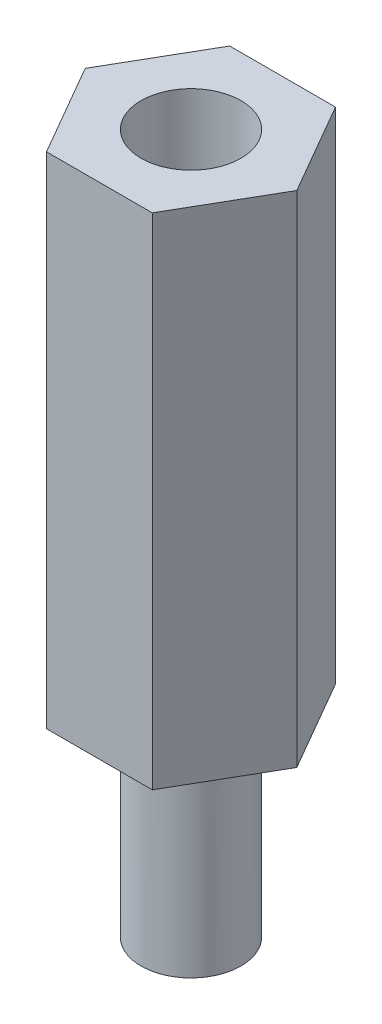
SolidWorks part; units mm, degrees
ref_plane "Plan de face" through (0, 0, 0) normal (0, 0, 1) x (1, 0, 0)
ref_plane "Plan de dessus" through (0, 0, 0) normal (0, 1, 0) x (1, 0, 0)
ref_plane "Plan de droite" through (0, 0, 0) normal (1, 0, 0) x (0, 0, -1)
sketch "Esquisse1" plane through (0, 0, 0) normal (0, 1, 0) x (1, 0, 0)
  line L0 (-3.1754, 0) -> (3.1754, 0) construction
  line L1 (1.5877, 2.75) -> (-1.5877, 2.75)
  line L2 (-1.5877, 2.75) -> (-3.1754, 0)
  line L3 (-3.1754, 0) -> (-1.5877, -2.75)
  line L4 (-1.5877, -2.75) -> (1.5877, -2.75)
  line L5 (1.5877, -2.75) -> (3.1754, 0)
  line L6 (3.1754, 0) -> (1.5877, 2.75)
  circle A0 centre (0, 0) radius 2.75 construction
  circle A1 centre (0, 0) radius 1.5
  dimension "D2" = 3
  dimension "D1" = 5.5
extrude "Boss.-Extru.1" add sketch "Esquisse1" along normal blind 15
sketch "Esquisse2" plane through (0, 0, 0) normal (0, -1, 0) x (1, 0, 0)
  circle A0 centre (0, 0) radius 1.5
  dimension "D1" = 3
extrude "Boss.-Extru.2" add sketch "Esquisse2" along normal blind 6 and the other way blind 1
